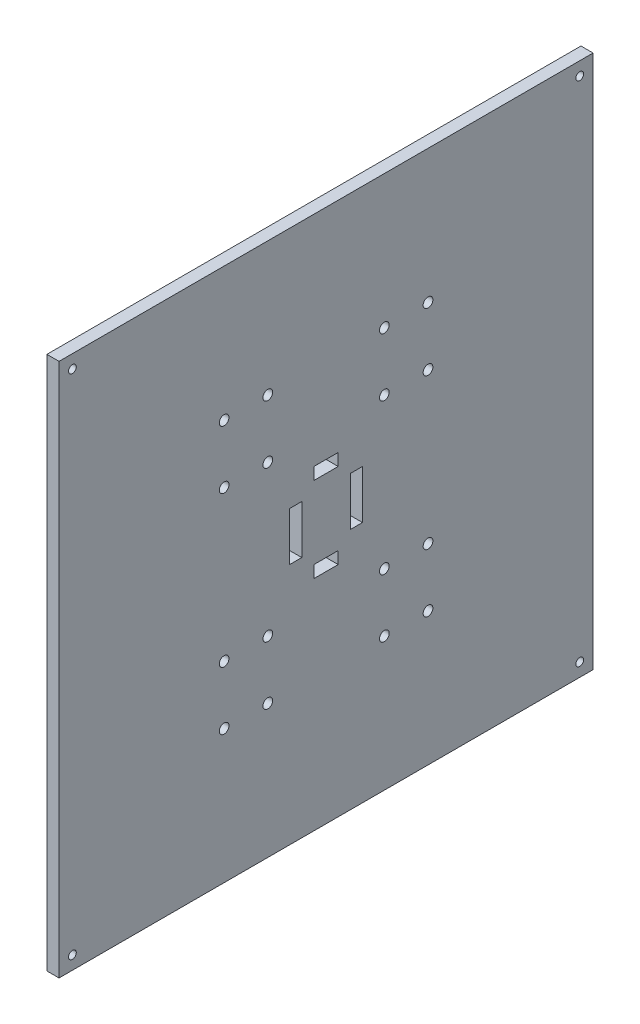
SolidWorks part; units mm, degrees
ref_plane "前视基准面" through (0, 0, 0) normal (0, 0, 1) x (1, 0, 0)
ref_plane "上视基准面" through (0, 0, 0) normal (0, 1, 0) x (1, 0, 0)
ref_plane "右视基准面" through (0, 0, 0) normal (1, 0, 0) x (0, 0, -1)
sketch "草图1" plane through (0, 0, 0) normal (1, 0, 0) x (0, 0, -1)
  line L0 (-81.4703, 19.8227) -> (104.7911, 19.8227) construction
  line L5 (-83.9428, -66.1773) -> (102.5933, -66.1773) construction
  line L6 (34.2401, 76.6568) -> (34.2401, -121.6924) construction
  line L7 (-31.7599, 78.8545) -> (-31.7599, -110.7035) construction
  line L13 (11.2401, -13.1773) -> (16.2401, -13.1773)
  line L17 (-13.7599, -13.1773) -> (-8.7599, -13.1773)
  line L18 (-13.7599, -13.1773) -> (-13.7599, -33.1773)
  line L19 (-13.7599, -33.1773) -> (-8.7599, -33.1773)
  line L20 (-8.7599, -13.1773) -> (-8.7599, -33.1773)
  line L21 (11.2401, -13.1773) -> (11.2401, -33.1773)
  line L22 (11.2401, -33.1773) -> (16.2401, -33.1773)
  line L23 (16.2401, -13.1773) -> (16.2401, -33.1773)
  line L24 (-92.2677, -23.1773) -> (98.2843, -23.1773) construction
  line L25 (-3.7599, -3.1773) -> (6.2401, -3.1773)
  line L26 (-3.7599, -3.1773) -> (-3.7599, -8.1798)
  line L27 (-3.7599, -8.1798) -> (6.2401, -8.1798)
  line L28 (6.2401, -3.1773) -> (6.2401, -8.1798)
  line L29 (-3.7599, -38.1773) -> (6.2401, -38.1773)
  line L30 (-3.7599, -38.1773) -> (-3.7599, -43.1773)
  line L31 (-3.7599, -43.1773) -> (6.2401, -43.1773)
  line L32 (6.2401, -38.1773) -> (6.2401, -43.1773)
  line L33 (1.2401, 71.4876) -> (1.2401, -97.6898) construction
  line L35 (111.2401, 86.8227) -> (-108.7599, 86.8227)
  line L36 (111.2401, 86.8227) -> (111.2401, -133.1773)
  line L37 (111.2401, -133.1773) -> (-108.7599, -133.1773)
  line L38 (-108.7599, 86.8227) -> (-108.7599, -133.1773)
  circle A0 centre (-22.7599, 7.8227) radius 2
  circle A1 centre (-40.7599, 7.8227) radius 2
  circle A2 centre (-40.7599, 31.8227) radius 2
  circle A3 centre (-22.7599, 31.8227) radius 2
  circle A4 centre (-22.7599, -78.1773) radius 2
  circle A5 centre (-40.7599, -78.1773) radius 2
  circle A6 centre (-40.7599, -54.1773) radius 2
  circle A7 centre (-22.7599, -54.1773) radius 2
  circle A8 centre (43.2401, 7.8227) radius 2
  circle A9 centre (25.2401, 7.8227) radius 2
  circle A10 centre (25.2401, 31.8227) radius 2
  circle A11 centre (43.2401, 31.8227) radius 2
  circle A12 centre (43.2401, -78.1773) radius 2
  circle A13 centre (25.2401, -78.1773) radius 2
  circle A14 centre (25.2401, -54.1773) radius 2
  circle A15 centre (43.2401, -54.1773) radius 2
  circle A16 centre (105.7401, 81.3227) radius 1.6
  circle A17 centre (-103.2599, 81.3227) radius 1.6
  circle A18 centre (-103.2599, -127.6773) radius 1.6
  circle A19 centre (105.7401, -127.6773) radius 1.6
  dimension "D7" = 4
  dimension "D8" = 4
  dimension "D9" = 4
  dimension "D10" = 4
  dimension "D15" = 4
  dimension "D16" = 4
  dimension "D17" = 4
  dimension "D18" = 4
  dimension "D23" = 4
  dimension "D24" = 4
  dimension "D25" = 4
  dimension "D26" = 4
  dimension "D31" = 4
  dimension "D32" = 4
  dimension "D33" = 4
  dimension "D34" = 4
  dimension "D52" = 3.2
  dimension "D53" = 3.2
  dimension "D54" = 3.2
  dimension "D55" = 3.2
  dimension "D3" = 86
  dimension "D4" = 66
  dimension "D6" = 20
  dimension "D11" = 18
  dimension "D12" = 18
  dimension "D13" = 24
  dimension "D14" = 24
  dimension "D19" = 18
  dimension "D20" = 18
  dimension "D21" = 24
  dimension "D22" = 24
  dimension "D27" = 18
  dimension "D28" = 18
  dimension "D29" = 24
  dimension "D30" = 24
  dimension "D35" = 18
  dimension "D36" = 18
  dimension "D37" = 24
  dimension "D38" = 24
  dimension "D39" = 12
  dimension "D40" = 9
  dimension "D41" = 9
  dimension "D42" = 9
  dimension "D43" = 12
  dimension "D44" = 12
  dimension "D45" = 9
  dimension "D46" = 9
  dimension "D47" = 12
  dimension "D48" = 9
  dimension "D49" = 12
  dimension "D50" = 95
  dimension "D51" = 90
  dimension "D56" = 209
  dimension "D57" = 209
  dimension "D58" = 20
  dimension "D59" = 5
  dimension "D60" = 5
  dimension "D61" = 10
  dimension "D62" = 10
  dimension "D63" = 5.0026
  dimension "D64" = 5
  dimension "D65" = 43
  dimension "D66" = 33
  dimension "D67" = 10
  dimension "D68" = 10
  dimension "D69" = 5
  dimension "D70" = 5
  dimension "D71" = 20
  dimension "D72" = 20
  dimension "D73" = 15
  dimension "D74" = 15
  dimension "D75" = 220
  dimension "D76" = 220
  dimension "D77" = 209
  dimension "D78" = 209
  dimension "D79" = 5.5
  dimension "D80" = 5.5
  dimension "D81" = 5.5
  dimension "D82" = 5.5
extrude "凸台-拉伸1" add sketch "草图1" along normal blind 5
